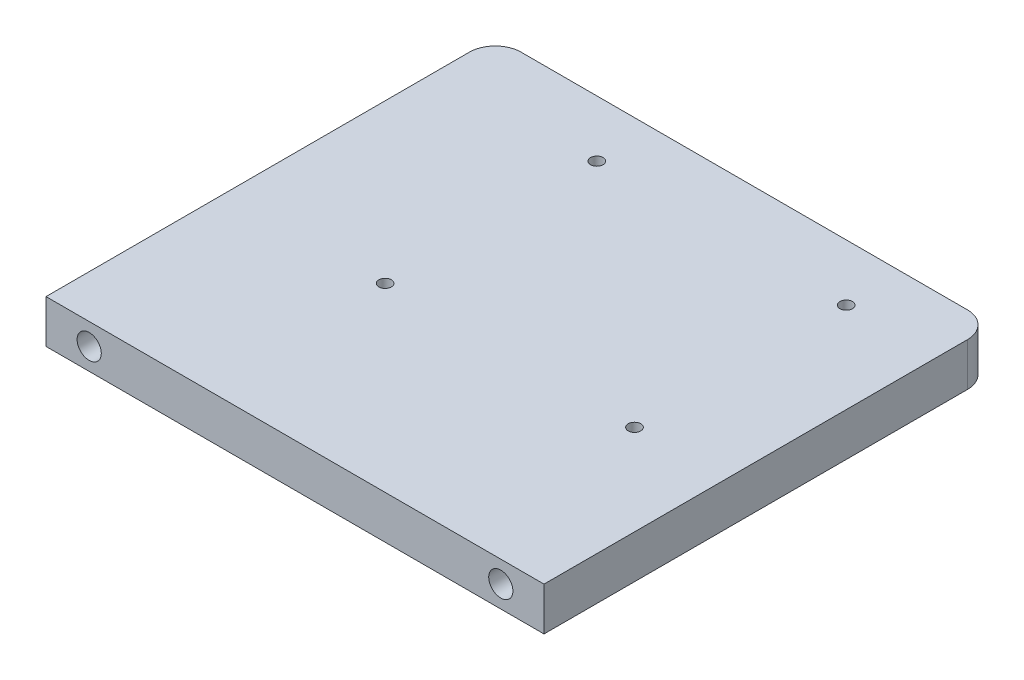
SolidWorks part; units mm, degrees
ref_plane "Front Plane" through (0, 0, 0) normal (0, 0, 1) x (1, 0, 0)
ref_plane "Top Plane" through (0, 0, 0) normal (0, 1, 0) x (1, 0, 0)
ref_plane "Right Plane" through (0, 0, 0) normal (1, 0, 0) x (0, 0, -1)
sketch "Sketch2" plane through (0, 0, 0) normal (0, 1, 0) x (1, 0, 0)
  line L0 (-5.5, 0) -> (5.5, 0) construction
  line L1 (-52.7926, 109.8893) -> (62.5, 109.8893)
  line L2 (-52.7926, 109.8893) -> (-52.7926, -24.1107)
  line L3 (-52.7926, -24.1107) -> (62.5, -24.1107)
  line L4 (62.5, 109.8893) -> (62.5, -24.1107)
  line L5 (0, -5.5) -> (0, 5.5) construction
  dimension "D1" = 109.8893
  dimension "D2" = 24.1107
  dimension "D3" = 62.5
  dimension "D4" = 52.7926
extrude "Boss-Extrude2" add sketch "Sketch2" along normal blind 8 contours L2 L1 L4 L3
fillet "Fillet2" radius 6 2 edges at (62.5, 4, -109.8893) (-52.7926, 4, -109.8893)
sketch "Sketch19" plane through (-52.7926, 0, 0) normal (-1, 0, 0) x (0, 0, 1)
  line L0 (24.1107, 8) -> (24.1107, 0) construction
  line L1 (24.1107, -36) -> (32.1107, -36)
  line L2 (24.1107, -36) -> (24.1107, 63)
  line L3 (24.1107, 63) -> (32.1107, 63)
  line L4 (32.1107, -36) -> (32.1107, 63)
  line L5 (-103.8893, 8) -> (24.1107, 8) construction
  line L6 (-103.8893, 0) -> (24.1107, 0) construction
  dimension "D1" = 8
  dimension "D2" = 55
  dimension "D3" = 36
extrude "Boss-Extrude3" add sketch "Sketch19" against normal up to surface (115.2926 mm away) up to face at (62.5, 4, -39.8893)
sketch "Sketch21" plane through (0, 0, 32.1107) normal (0, 0, 1) x (1, 0, 0)
  line L0 (72.5, 73) -> (-62.7926, 73)
  line L1 (-62.7926, 73) -> (-62.7926, -56)
  line L2 (-62.7926, -56) -> (72.5, -56)
  line L3 (72.5, -56) -> (72.5, 73)
  line L4 (-52.7926, -36) -> (62.5, -36)
  line L5 (62.5, -36) -> (62.5, 63)
  line L6 (62.5, 63) -> (-52.7926, 63)
  line L7 (-52.7926, 63) -> (-52.7926, -36)
  line L8 (-52.7926, -36) -> (62.5, -36)
  line L9 (62.5, -36) -> (62.5, 63)
  line L10 (62.5, 63) -> (-52.7926, 63)
  line L11 (-52.7926, 63) -> (-52.7926, -36)
  line L12 (62.5, -36) -> (-52.7926, -36) construction
  dimension "D3" = 10
  dimension "D2" = 10
  dimension "D4" = 10
  dimension "D5" = 20
  dimension "D1" = 0
extrude "Boss-Extrude4" add sketch "Sketch21" against normal up to surface (8 mm away) up to face at (4.8537, 35.5, 24.1107)
fillet "Fillet3" radius 5 4 edges at (-62.7926, 73, 28.1107) (72.5, 73, 28.1107) (72.5, -56, 28.1107) (-62.7926, -56, 28.1107)
sketch "Sketch22" plane through (0, 0, 24.1107) normal (0, 0, -1) x (-1, 0, 0)
  line L0 (57.7926, 69.75) -> (-67.5, 69.75)
  line L1 (-69.25, 68) -> (-69.25, -51)
  line L2 (-67.5, -52.75) -> (57.7926, -52.75)
  line L3 (59.5426, -51) -> (59.5426, 68)
  line L4 (62.7926, -51) -> (62.7926, 68)
  line L5 (57.7926, 73) -> (-67.5, 73)
  line L6 (-72.5, 68) -> (-72.5, -51)
  line L7 (-67.5, -56) -> (57.7926, -56)
  line L8 (62.7926, -51) -> (62.7926, 68)
  line L9 (57.7926, 73) -> (-67.5, 73)
  line L10 (-72.5, 68) -> (-72.5, -51)
  line L11 (-67.5, -56) -> (57.7926, -56)
  arc A0 (-67.5, 69.75) -> (-69.25, 68) centre (-67.5, 68) ccw
  arc A1 (-69.25, -51) -> (-67.5, -52.75) centre (-67.5, -51) ccw
  arc A2 (57.7926, -52.75) -> (59.5426, -51) centre (57.7926, -51) ccw
  arc A3 (59.5426, 68) -> (57.7926, 69.75) centre (57.7926, 68) ccw
  arc A4 (62.7926, 68) -> (57.7926, 73) centre (57.7926, 68) ccw
  arc A5 (-67.5, 73) -> (-72.5, 68) centre (-67.5, 68) ccw
  arc A6 (-72.5, -51) -> (-67.5, -56) centre (-67.5, -51) ccw
  arc A7 (57.7926, -56) -> (62.7926, -51) centre (57.7926, -51) ccw
  arc A8 (62.7926, 68) -> (57.7926, 73) centre (57.7926, 68) ccw
  arc A9 (-67.5, 73) -> (-72.5, 68) centre (-67.5, 68) ccw
  arc A10 (-72.5, -51) -> (-67.5, -56) centre (-67.5, -51) ccw
  arc A11 (57.7926, -56) -> (62.7926, -51) centre (57.7926, -51) ccw
  dimension "D1" = 0
  dimension "D2" = 3.25
extrude "Cut-Extrude1" cut sketch "Sketch22" against normal blind 4
sketch "Sketch24" plane through (0, 0, 24.1107) normal (0, 0, -1) x (-1, 0, 0)
  line L0 (-62.5, 8) -> (-62.5, 69.75) construction
  line L1 (57.7926, 69.75) -> (-67.5, 69.75) construction
  line L2 (52.7926, 8) -> (52.7926, 69.75) construction
  line L3 (-62.5, 55) -> (52.7926, 55) construction
  line L4 (52.7926, 8) -> (-62.5, 8) construction
  line L6 (-62.5, 55) -> (52.7926, 55)
  line L7 (-62.5, 55) -> (-62.5, 65)
  line L8 (-62.5, 65) -> (52.7926, 65)
  line L9 (52.7926, 55) -> (52.7926, 65)
  dimension "D1" = 47
  dimension "D2" = 10
extrude "Boss-Extrude5" add sketch "Sketch24" along normal blind 104
fillet "Fillet4" radius 6 2 edges at (62.5, 60, -79.8893) (-52.7926, 60, -79.8893)
sketch "Sketch42" plane through (0, 55, 0) normal (0, -1, 0) x (-1, 0, 0)
  line L0 (-41.5424, 17.7893) -> (16.1876, 17.7893) construction
  line L2 (52.7926, 73.8893) -> (52.7926, -24.1107) construction
  line L3 (16.1876, 66.7993) -> (16.1876, 17.7893) construction
  line L5 (-62.5, -24.1107) -> (52.7926, -24.1107) construction
  line L6 (16.1876, 66.7993) -> (-41.5424, 66.7993) construction
  line L7 (-41.5424, 66.7993) -> (-41.5424, 17.7893) construction
  dimension "D1" = 36.605
  dimension "D2" = 41.9
  dimension "D3" = 49.01
  dimension "D4" = 57.73
hole_wizard "CSK for M2.5 Flat Head Machine Screw2" positions "Sketch45" profile "Sketch46" countersink size "M2.5" standard "ANSI Metric"
sketch "Sketch45" plane through (0, 55, 0) normal (0, -1, 0) x (-1, 0, 0)
  point P0 (16.1876, 66.7993)
  point P3 (-41.5424, 66.7993)
  point P6 (16.1876, 17.7893)
  point P9 (-41.5424, 17.7893)
sketch "Sketch46" plane through (-16.1876, 55, -66.7993) normal (1, 0, 0) x (0, 0, -1)
  line L0 (0, 0) -> (0, 10)
  line L1 (0, 10) -> (1.45, 10)
  line L2 (1.45, 10) -> (1.45, 1.3)
  line L3 (1.45, 1.3) -> (2.75, 0)
  line L5 (2.75, 0) -> (0, 0)
  line L6 (-1.45, 1.3) -> (-2.75, 0) construction
  line L11 (0, -6.35) -> (0, 107.95) construction
  dimension "Thru Hole Dia." = 2.9
  dimension "Thru Hole Depth" = 10
  dimension "Near C'Sink Dia." = 5.5
  dimension "Near C'Sink Angle" = 90
sketch "Sketch49" plane through (0, 0, 32.1107) normal (0, 0, 1) x (1, 0, 0)
  line L0 (4.8537, 40.1596) -> (4.8537, -56) construction
  line L2 (-57.7926, -56) -> (67.5, -56) construction
  line L3 (-62.7926, 40.1596) -> (4.8537, 40.1596) construction
  line L4 (-62.7926, 68) -> (-62.7926, -51) construction
  circle A0 centre (4.8537, 40.1596) radius 4.43
  dimension "D1" = 8.86
extrude "Cut-Extrude3" cut sketch "Sketch49" against normal up to surface (8 mm away) up to face at (4.8537, 4, 24.1107)
hole_wizard "M2.5 Clearance Hole1" positions "Sketch58" profile "Sketch59" hole size "M2.5" standard "ANSI Metric" end condition through all
sketch "Sketch58" plane through (0, 8, 0) normal (0, 1, 0) x (1, 0, 0)
  line L0 (-28.27, 101.64) -> (-7.29, 101.64) construction
  line L1 (-7.29, 101.64) -> (-7.29, 88.14) construction
  line L2 (-7.29, 88.14) -> (-28.27, 88.14) construction
  line L3 (-28.27, 88.14) -> (-28.27, 101.64) construction
  line L6 (-5.5, 0) -> (5.5, 0) construction
  line L7 (0, -5.5) -> (0, 5.5) construction
  point P0 (-28.27, 101.64)
  point P2 (-7.29, 101.64)
  point P4 (-7.29, 88.14)
  point P6 (-28.27, 88.14)
  dimension "D1" = 88.14
  dimension "D2" = 28.27
  dimension "D3" = 7.29
  dimension "D4" = 101.64
sketch "Sketch59" plane through (-28.27, 8, -101.64) normal (1, 0, 0) x (0, 0, 1)
  line L0 (0, 0) -> (0, 64)
  line L1 (0, 64) -> (1.45, 64)
  line L2 (1.45, 64) -> (1.45, 0)
  line L5 (1.45, 0) -> (0, 0)
  line L11 (0, -6.35) -> (0, 107.95) construction
  dimension "Thru Hole Dia." = 2.9
  dimension "Thru Hole Depth" = 64
sketch "Sketch60" plane through (0, 8, 0) normal (0, 1, 0) x (1, 0, 0)
  line L0 (-30.27, 101.64) -> (-26.27, 101.64) construction
  line L1 (-30.27, 103.09) -> (-26.27, 103.09)
  line L2 (-30.27, 100.19) -> (-26.27, 100.19)
  line L3 (-9.29, 101.64) -> (-5.29, 101.64) construction
  line L4 (-9.29, 103.09) -> (-5.29, 103.09)
  line L5 (-9.29, 100.19) -> (-5.29, 100.19)
  line L6 (-30.27, 88.14) -> (-26.27, 88.14) construction
  line L7 (-30.27, 89.59) -> (-26.27, 89.59)
  line L8 (-30.27, 86.69) -> (-26.27, 86.69)
  line L9 (-9.29, 88.14) -> (-5.29, 88.14) construction
  line L10 (-9.29, 89.59) -> (-5.29, 89.59)
  line L11 (-9.29, 86.69) -> (-5.29, 86.69)
  arc A0 (-30.27, 103.09) -> (-30.27, 100.19) centre (-30.27, 101.64) ccw
  arc A1 (-26.27, 100.19) -> (-26.27, 103.09) centre (-26.27, 101.64) ccw
  arc A2 (-9.29, 103.09) -> (-9.29, 100.19) centre (-9.29, 101.64) ccw
  arc A3 (-5.29, 100.19) -> (-5.29, 103.09) centre (-5.29, 101.64) ccw
  arc A4 (-30.27, 89.59) -> (-30.27, 86.69) centre (-30.27, 88.14) ccw
  arc A5 (-26.27, 86.69) -> (-26.27, 89.59) centre (-26.27, 88.14) ccw
  arc A6 (-9.29, 89.59) -> (-9.29, 86.69) centre (-9.29, 88.14) ccw
  arc A7 (-5.29, 86.69) -> (-5.29, 89.59) centre (-5.29, 88.14) ccw
  circle A8 centre (-28.27, 101.64) radius 1.45 construction
  point P2 (-28.27, 101.64)
  point P9 (-7.29, 101.64)
  point P17 (-28.27, 88.14)
  point P25 (-7.29, 88.14)
  dimension "D1" = 4
extrude "Cut-Extrude4" cut sketch "Sketch60" against normal up to next
chamfer "Chamfer1" distance 0.9 angle 45 16 edges at (-7.29, 8, -100.19) (-3.84, 8, -101.64) (-10.74, 8, -101.64) (-7.29, 8, -103.09) (-7.29, 8, -86.69) (-3.84, 8, -88.14) (-10.74, 8, -88.14) (-7.29, 8, -89.59) (-28.27, 8, -86.69) (-24.82, 8, -88.14) (-31.72, 8, -88.14) (-28.27, 8, -89.59) (-28.27, 8, -103.09) (-31.72, 8, -101.64) (-24.82, 8, -101.64) (-28.27, 8, -100.19)
sketch "Sketch62" plane through (-52.7926, 0, 0) normal (-1, 0, 0) x (0, 0, 1)
  line L1 (-109.8893, 8) -> (24.1107, 8)
  line L2 (-109.8893, 8) -> (-109.8893, 0)
  line L3 (-109.8893, 0) -> (24.1107, 0)
  line L4 (24.1107, 8) -> (24.1107, 0)
extrude "Cut-Extrude5" cut sketch "Sketch62" against normal up to surface (115.2926 mm away) up to face at (62.5, 4, -39.8893)
sketch "Sketch63" plane through (0, 73, 0) normal (0, 1, 0) x (1, 0, 0)
  line L0 (72.5, -28.1107) -> (72.5, -32.1107) construction
  line L1 (-62.7926, -32.1107) -> (72.5, -32.1107)
  line L2 (-62.7926, -32.1107) -> (-62.7926, -24.1107)
  line L3 (-62.7926, -24.1107) -> (72.5, -24.1107)
  line L4 (72.5, -32.1107) -> (72.5, -24.1107)
  line L5 (-57.7926, -24.1107) -> (67.5, -24.1107) construction
extrude "Cut-Extrude6" cut sketch "Sketch63" against normal up to surface (129 mm away) up to face at (4.8537, -56, 30.1107)
hole_wizard "Ø5.6 (5.6) Diameter Hole1" positions "Sketch65" profile "Sketch66" hole size "Ø5.6" standard "ANSI Metric"
sketch "Sketch65" plane through (0, 0, 24.1107) normal (0, 0, 1) x (1, 0, 0)
  line L0 (-52.7926, 55) -> (-52.7926, 65) construction
  line L1 (-52.7926, 65) -> (62.5, 65) construction
  line L2 (62.5, 65) -> (62.5, 55) construction
  point P0 (-42.7926, 60)
  point P7 (52.5, 60)
  dimension "D1" = 10
  dimension "D2" = 5
  dimension "D3" = 10
sketch "Sketch66" plane through (-42.7926, 60, 24.1107) normal (1, 0, 0) x (0, -1, 0)
  line L0 (0, 0) -> (0, 9.6824)
  line L1 (0, 9.6824) -> (2.8, 8)
  line L2 (2.8, 8) -> (2.8, 0)
  line L5 (2.8, 0) -> (0, 0)
  line L10 (0, 9.6824) -> (-2.8, 8) construction
  line L11 (0, -6.35) -> (0, 107.95) construction
  dimension "Hole Dia." = 5.6
  dimension "Hole Depth" = 8
  dimension "Drill Angle" = 118
